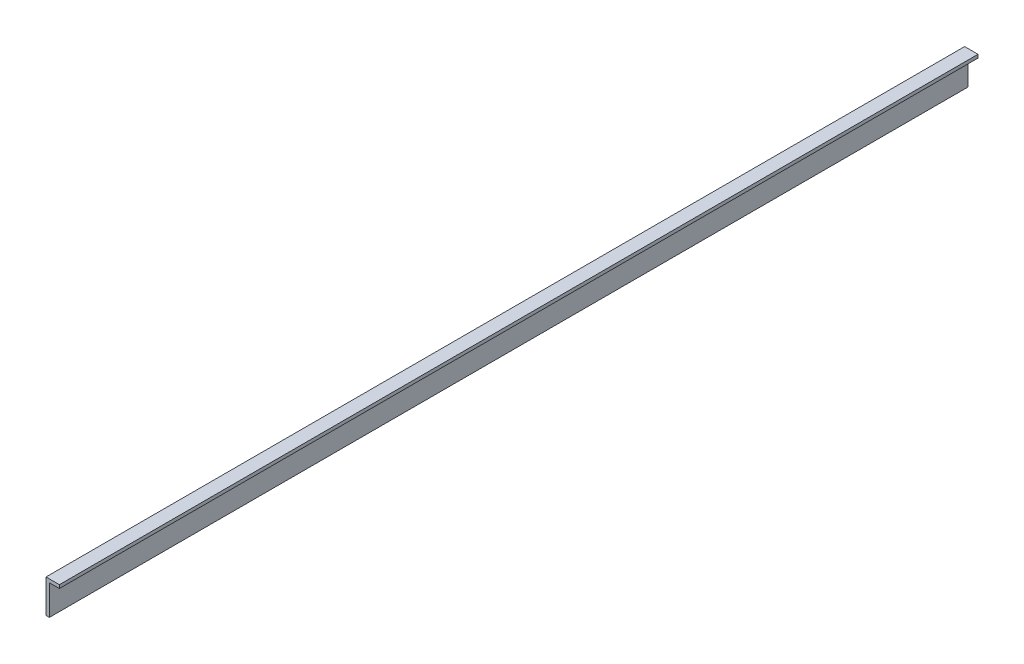
SolidWorks part; units mm, degrees
ref_plane "Front Plane" through (0, 0, 0) normal (0, 0, 1) x (1, 0, 0)
ref_plane "Top Plane" through (0, 0, 0) normal (0, 1, 0) x (1, 0, 0)
ref_plane "Right Plane" through (0, 0, 0) normal (1, 0, 0) x (0, 0, -1)
other "Configuration Table"
sketch "Sketch1" plane through (0, 0, 0) normal (0, 0, 1) x (1, 0, 0)
  line L0 (56, 870) -> (54, 870)
  line L1 (54, 870) -> (54, 890)
  line L2 (54, 890) -> (62, 890)
  line L3 (62, 890) -> (62, 888)
  line L4 (62, 888) -> (56, 888)
  line L5 (56, 888) -> (56, 870)
extrude "OVEN_yag_kabi_L_raf_sol_1" add sketch "Sketch1" against normal blind 550 from offset 30 separate body
